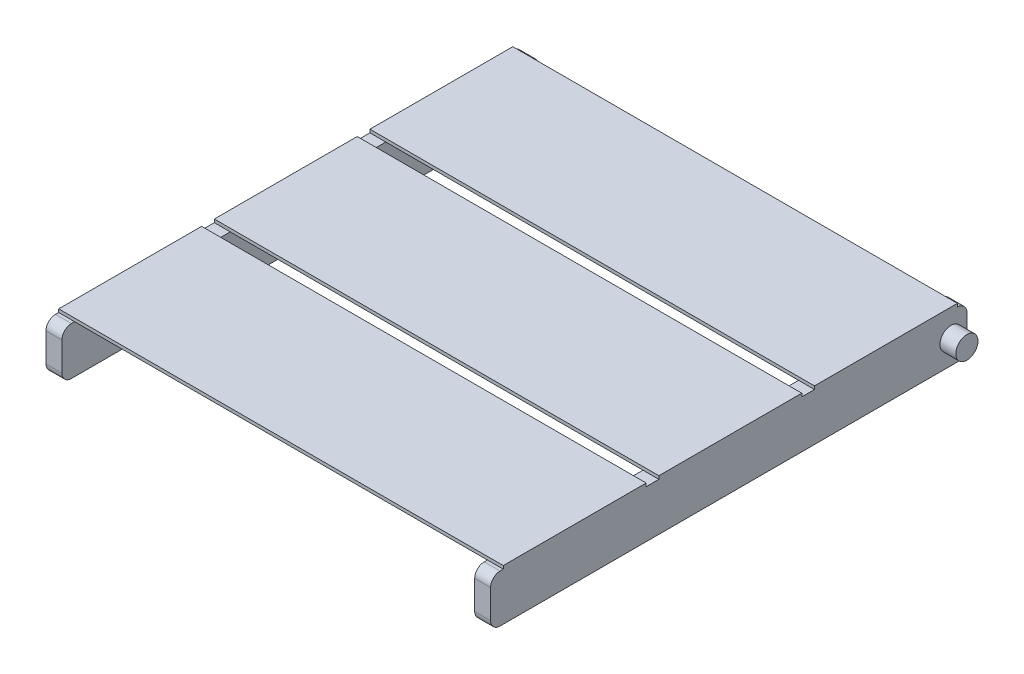
SolidWorks part; units mm, degrees
ref_plane "Front Plane" through (0, 0, 0) normal (0, 0, 1) x (1, 0, 0)
ref_plane "Top Plane" through (0, 0, 0) normal (0, 1, 0) x (1, 0, 0)
ref_plane "Right Plane" through (0, 0, 0) normal (1, 0, 0) x (0, 0, -1)
sketch "Sketch1" plane through (0, 0, 0) normal (1, 0, 0) x (0, 0, -1)
  line L1 (-720, -75) -> (720, -75)
  line L2 (-750, -45) -> (-750, 45)
  line L3 (-720, 75) -> (720, 75)
  line L4 (750, -45) -> (750, 45)
  line L5 (-750, -75) -> (750, 75) construction
  line L6 (-750, 75) -> (750, -75) construction
  arc A0 (720, -75) -> (750, -45) centre (720, -45) ccw
  arc A1 (720, 75) -> (750, 45) centre (720, 45) cw
  arc A2 (-720, -75) -> (-750, -45) centre (-720, -45) cw
  arc A3 (-750, 45) -> (-720, 75) centre (-720, 45) cw
  point P0 (0, 0)
  dimension "D3" = 30
  dimension "D1" = 150
  dimension "D2" = 1500
extrude "Boss-Extrude1" add sketch "Sketch1" along normal blind 50
sketch "Sketch2" plane through (0, 75, 0) normal (0, 1, 0) x (1, 0, 0)
  line L1 (1400, 270) -> (0, 270)
  line L2 (1400, 270) -> (1400, 720)
  line L3 (1400, 720) -> (0, 720)
  line L4 (0, 270) -> (0, 720)
  line L5 (1400, 270) -> (0, 720) construction
  line L6 (1400, 720) -> (0, 270) construction
  point P0 (700, 495)
  dimension "D1" = 1400
  dimension "D2" = 450
extrude "Boss-Extrude2" add sketch "Sketch2" along normal blind 10
pattern_linear "LPattern1" count 2 spacing 1350 along (1, 0, 0) of "Boss-Extrude1"
pattern_linear "LPattern2" count 3 spacing 490 along (0, 0, 1) of "Boss-Extrude2"
sketch "Sketch3" plane through (0, 0, 0) normal (-1, 0, 0) x (0, 0, 1)
  line L0 (-750, -45) -> (-750, 45) construction
  circle A0 centre (-700, 0) radius 35
  dimension "D1" = 70
  dimension "D2" = 50
extrude "Boss-Extrude3" add sketch "Sketch3" along normal blind 50
pattern_linear "LPattern3" count 2 spacing 1450 along (1, 0, 0) of "Boss-Extrude3"
